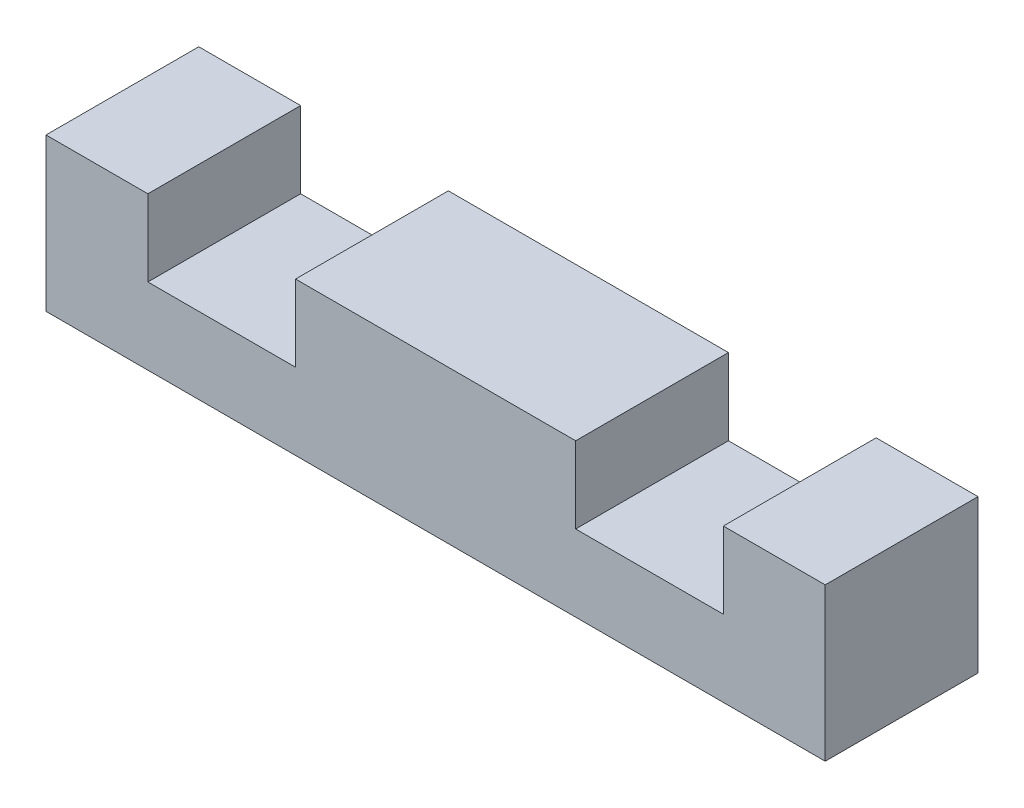
SolidWorks part; units mm, degrees
ref_plane "Plan de face" through (0, 0, 0) normal (0, 0, 1) x (1, 0, 0)
ref_plane "Plan de dessus" through (0, 0, 0) normal (0, 1, 0) x (1, 0, 0)
ref_plane "Plan de droite" through (0, 0, 0) normal (1, 0, 0) x (0, 0, -1)
sketch "Esquisse1" plane through (0, 0, 0) normal (0, 0, 1) x (1, 0, 0)
  line L0 (0, 0) -> (0, 6)
  line L1 (0, 6) -> (4, 6)
  line L2 (4, 6) -> (4, 3)
  line L3 (4, 3) -> (9.8, 3)
  line L4 (9.8, 3) -> (9.8, 6)
  line L5 (9.8, 6) -> (20.8, 6)
  line L6 (20.8, 6) -> (20.8, 3)
  line L7 (20.8, 3) -> (26.6, 3)
  line L8 (26.6, 3) -> (26.6, 6)
  line L9 (26.6, 6) -> (30.6, 6)
  line L10 (30.6, 6) -> (30.6, 0)
  line L11 (30.6, 0) -> (0, 0)
  line L12 (6.9, 3) -> (6.9, 9.1845) construction
  line L14 (23.7, 3) -> (23.7, 9.1845) construction
  dimension "D1" = 6
  dimension "D2" = 3
  dimension "D3" = 5.8
  dimension "D4" = 5.8
  dimension "D5" = 16.8
  dimension "D6" = 4
  dimension "D7" = 4
extrude "Boss.-Extru.1" add sketch "Esquisse1" along normal blind 6
